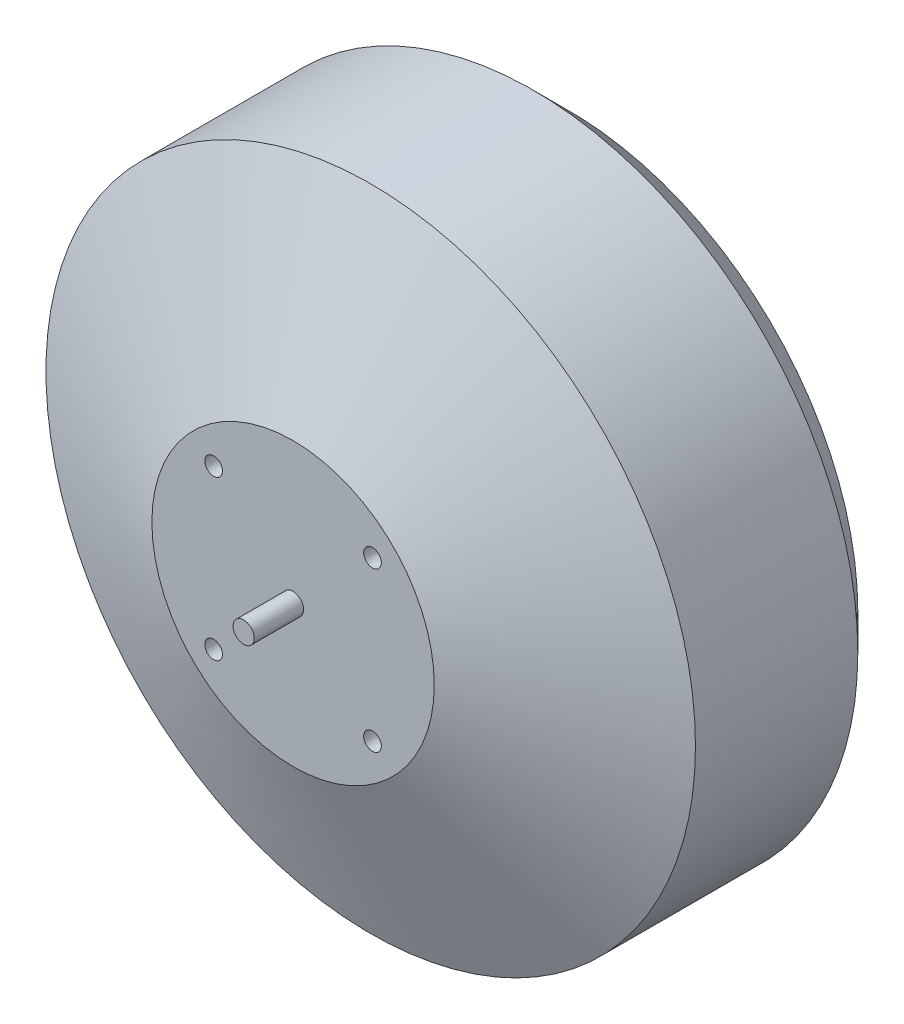
SolidWorks part; units mm, degrees
ref_plane "Front Plane" through (0, 0, 0) normal (0, 0, 1) x (1, 0, 0)
ref_plane "Top Plane" through (0, 0, 0) normal (0, 1, 0) x (1, 0, 0)
ref_plane "Right Plane" through (0, 0, 0) normal (1, 0, 0) x (0, 0, -1)
sketch "Sketch1" plane through (0, 0, 0) normal (1, 0, 0) x (0, 0, -1)
  line L0 (0, 46) -> (-28, 46)
  line L1 (-28, 46) -> (-39, 20)
  line L2 (-39, 20) -> (-39, 0)
  line L3 (-1764.481, 0) -> (86459.5709, 0) construction
  line L4 (0, 46) -> (0, 0)
  line L5 (-39, 0) -> (0, 0)
  dimension "D1" = 92
  dimension "D2" = 40
  dimension "D3" = 39
  dimension "D4" = 28
revolve "Body" add sketch "Sketch1" angle 360 about L3
sketch "Sketch2" plane through (0, 0, 39) normal (0, 0, 1) x (1, 0, 0)
  line L1 (11.25, -11.25) -> (-11.25, -11.25) construction
  line L2 (11.25, -11.25) -> (11.25, 11.25) construction
  line L3 (11.25, 11.25) -> (-11.25, 11.25) construction
  line L4 (-11.25, -11.25) -> (-11.25, 11.25) construction
  line L5 (11.25, -11.25) -> (-11.25, 11.25) construction
  line L6 (11.25, 11.25) -> (-11.25, -11.25) construction
  circle A0 centre (-11.25, 11.25) radius 1.25
  circle A1 centre (11.25, 11.25) radius 1.25
  circle A2 centre (11.25, -11.25) radius 1.25
  circle A3 centre (-11.25, -11.25) radius 1.25
  point P0 (0, 0)
  dimension "D2" = 2.5
  dimension "D1" = 22.5
extrude "Rotor_Holes" cut sketch "Sketch2" against normal blind 10
sketch "Sketch4" plane through (0, 0, 0) normal (0, 0, -1) x (-1, 0, 0)
  line L1 (14.25, -14.25) -> (-14.25, -14.25) construction
  line L2 (14.25, -14.25) -> (14.25, 14.25) construction
  line L3 (14.25, 14.25) -> (-14.25, 14.25) construction
  line L4 (-14.25, -14.25) -> (-14.25, 14.25) construction
  line L5 (14.25, -14.25) -> (-14.25, 14.25) construction
  line L6 (14.25, 14.25) -> (-14.25, -14.25) construction
  circle A0 centre (-14.25, 14.25) radius 1.75
  circle A1 centre (14.25, 14.25) radius 1.75
  circle A2 centre (14.25, -14.25) radius 1.75
  circle A3 centre (-14.25, -14.25) radius 1.75
  point P0 (0, 0)
  dimension "D2" = 3.5
  dimension "D1" = 28.5
extrude "Stator_Holes" cut sketch "Sketch4" against normal blind 10
sketch "Sketch5" plane through (0, 0, 0) normal (0, 0, -1) x (-1, 0, 0)
  circle A0 centre (0, 0) radius 1.75
  dimension "D1" = 3.5
extrude "Hole" cut sketch "Sketch5" against normal blind 5
fillet "Fillet1" radius 1 1 edges at (-1.75, 0, 0)
sketch "Sketch6" plane through (0, 0, 39) normal (0, 0, 1) x (1, 0, 0)
  circle A0 centre (0, 0) radius 1.5
  dimension "D1" = 3
extrude "Shaft" add sketch "Sketch6" along normal blind 7
chamfer "Chamfer1" distance 5 angle 45 1 edges at (46, 0, 0)
